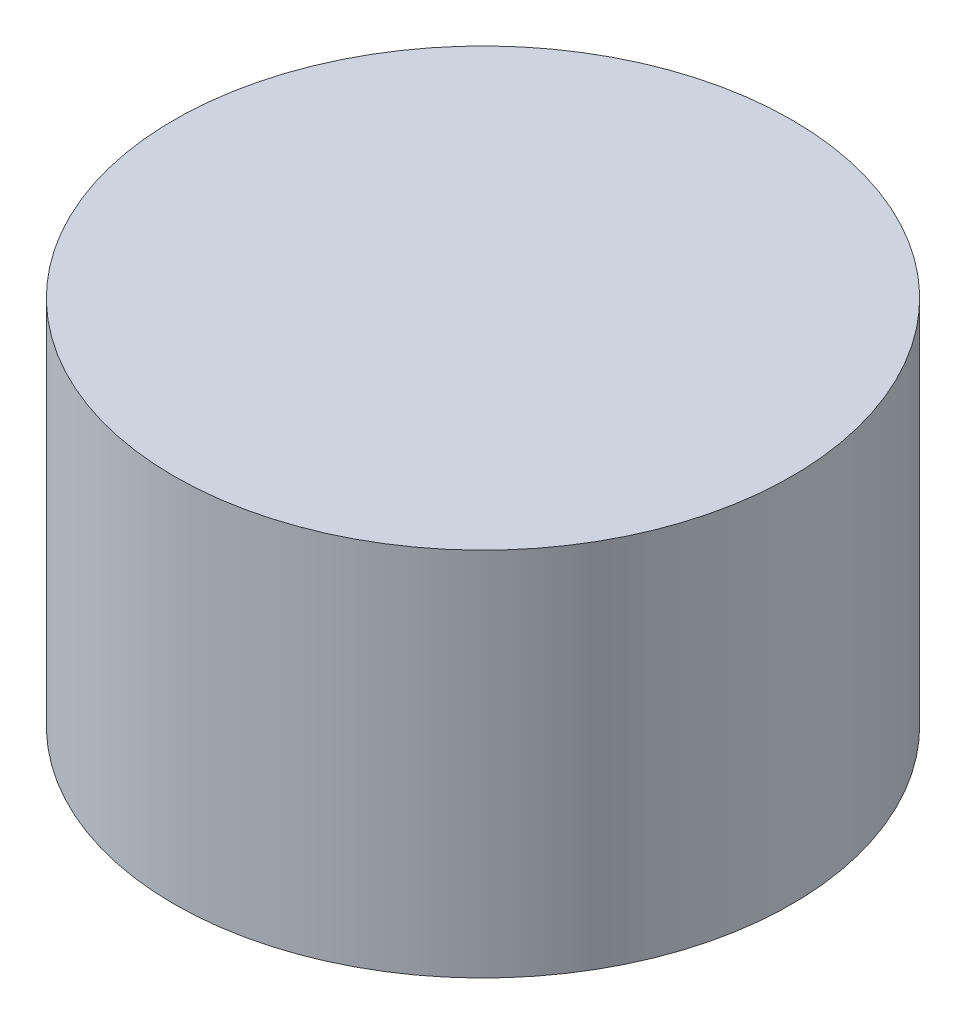
SolidWorks part; units mm, degrees
ref_plane "Front Plane" through (0, 0, 0) normal (0, 0, 1) x (1, 0, 0)
ref_plane "Top Plane" through (0, 0, 0) normal (0, 1, 0) x (1, 0, 0)
ref_plane "Right Plane" through (0, 0, 0) normal (1, 0, 0) x (0, 0, -1)
sketch "Sketch1" plane through (0, 0, 0) normal (0, 1, 0) x (1, 0, 0)
  circle A0 centre (-33.2362, 21.4386) radius 2.5
extrude "Boss-Extrude1" add sketch "Sketch1" along normal blind 3
